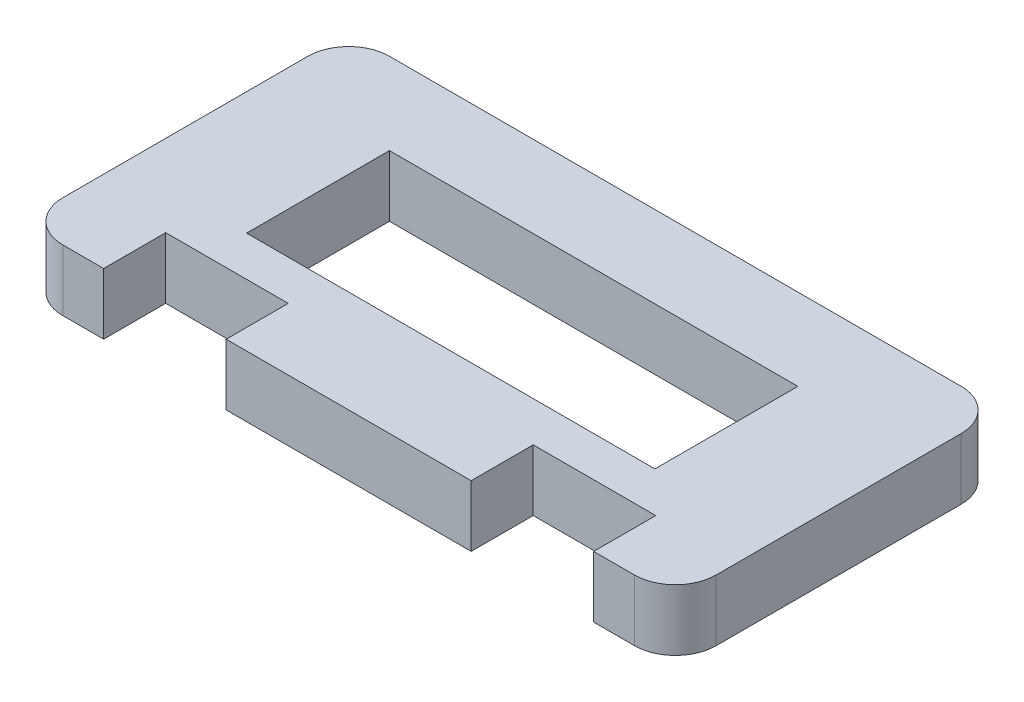
SolidWorks part; units mm, degrees
ref_plane "Front Plane" through (0, 0, 0) normal (0, 0, 1) x (1, 0, 0)
ref_plane "Top Plane" through (0, 0, 0) normal (0, 1, 0) x (1, 0, 0)
ref_plane "Right Plane" through (0, 0, 0) normal (1, 0, 0) x (0, 0, -1)
sketch "Sketch1" plane through (0, 0, 0) normal (0, 1, 0) x (1, 0, 0)
  line L0 (15, -12.4) -> (30, -12.4)
  line L1 (-35, 20) -> (35, 20)
  line L2 (-40, 15) -> (-40, -15)
  line L3 (-35, -20) -> (-30, -20)
  line L4 (40, 15) -> (40, -15)
  line L5 (-40, 20) -> (40, -20) construction
  line L6 (-40, -20) -> (40, 20) construction
  line L7 (-25, 10) -> (25, 10)
  line L8 (-25, 10) -> (-25, -7.5)
  line L9 (-25, -7.5) -> (25, -7.5)
  line L10 (25, 10) -> (25, -7.5)
  line L12 (-15, -12.4) -> (-15, -20)
  line L14 (-30, -20) -> (-30, -12.4)
  line L15 (-30, -12.4) -> (-15, -12.4)
  line L16 (30, -20) -> (30, -12.4)
  line L17 (30, -20) -> (35, -20)
  line L18 (-15, -20) -> (15, -20)
  line L19 (15, -12.4) -> (15, -20)
  arc A0 (-40, -15) -> (-35, -20) centre (-35, -15) ccw
  arc A1 (35, -20) -> (40, -15) centre (35, -15) ccw
  arc A2 (35, 20) -> (40, 15) centre (35, 15) cw
  arc A3 (-35, 20) -> (-40, 15) centre (-35, 15) ccw
  point P0 (0, 0)
  point P18 (0, 0)
  dimension "D3" = 5
  dimension "D1" = 40
  dimension "D2" = 80
  dimension "D4" = 50
  dimension "D5" = 17.5
  dimension "D6" = 60
  dimension "D7" = 7.6
  dimension "D8" = 10
  dimension "D9" = 10
  dimension "D10" = 15
  dimension "D11" = 15
extrude "Boss-Extrude1" add sketch "Sketch1" along normal blind 7.5 contours L2 A0 L3 L14 L15 L16 L17 A1 L4 A2 L1 A3
